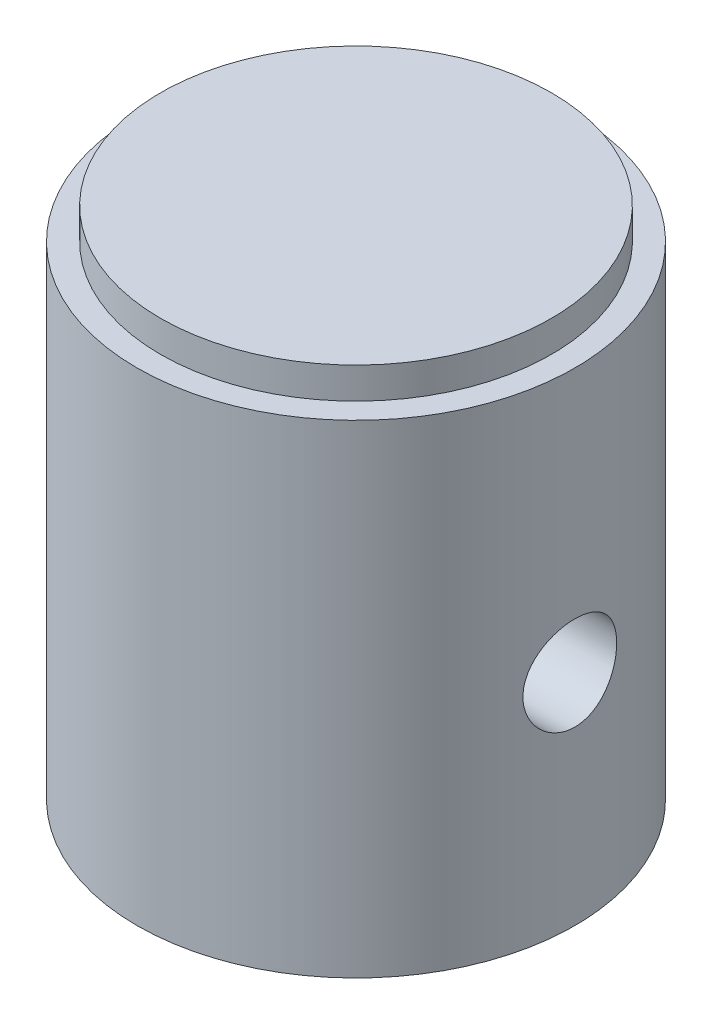
SolidWorks part; units mm, degrees
ref_plane "Front Plane" through (0, 0, 0) normal (0, 0, 1) x (1, 0, 0)
ref_plane "Top Plane" through (0, 0, 0) normal (0, 1, 0) x (1, 0, 0)
ref_plane "Right Plane" through (0, 0, 0) normal (1, 0, 0) x (0, 0, -1)
sketch "Sketch1" plane through (0, 0, 0) normal (0, 0, 1) x (1, 0, 0)
  line L0 (0, 0) -> (-6.25, 0)
  line L1 (-6.25, 0) -> (-6.25, -1)
  line L2 (-6.25, -1) -> (-7, -1)
  line L3 (-7, -1) -> (-7, -16.4461)
  line L4 (-7, -16.4461) -> (-6.2, -16.4461)
  line L5 (-6.2, -16.4461) -> (-4.25, -11.0885)
  line L6 (-4.25, -11.0885) -> (-4.25, -5.4461)
  line L7 (-4.25, -5.4461) -> (0, -2.8924)
  line L8 (0, -2.8924) -> (0, 0)
  line L9 (0, 0) -> (0, -21.7172) construction
  dimension "D1" = 7
  dimension "D2" = 6.25
  dimension "D3" = 1
  dimension "D4" = 11
  dimension "D5" = 59
  dimension "D6" = 20
  dimension "D7" = 4.25
  dimension "D8" = 6.2
revolve "Revolve1" add sketch "Sketch1" angle 360 about L9
sketch "Sketch2" plane through (0, 0, 0) normal (1, 0, 0) x (0, 0, -1)
  line L0 (0, -9.4461) -> (0, -16.4461) construction
  line L1 (-7, -16.4461) -> (7, -16.4461) construction
  circle A0 centre (0, -9.4461) radius 1.5
  dimension "D1" = 3
  dimension "D2" = 7
extrude "Cut-Extrude1" cut sketch "Sketch2" against normal through all both and the other way through all
